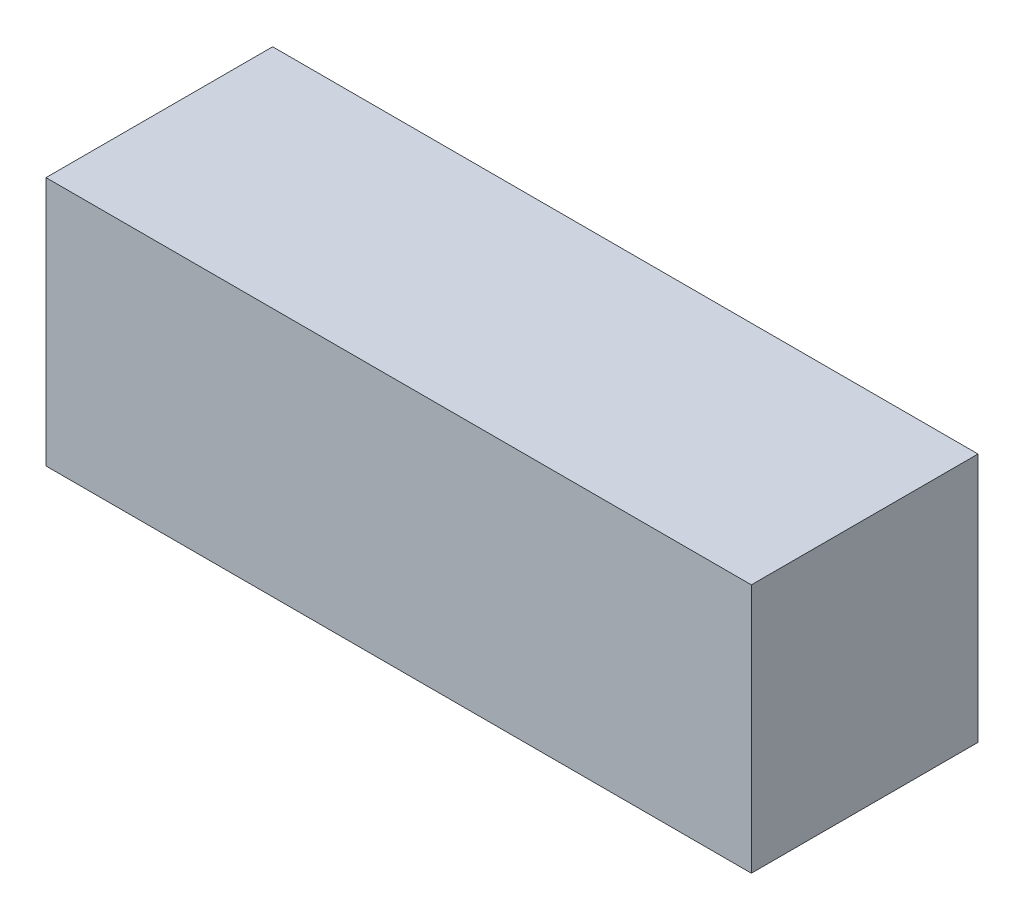
SolidWorks part; units mm, degrees
ref_plane "Front Plane" through (0, 0, 0) normal (0, 0, 1) x (1, 0, 0)
ref_plane "Top Plane" through (0, 0, 0) normal (0, 1, 0) x (1, 0, 0)
ref_plane "Right Plane" through (0, 0, 0) normal (1, 0, 0) x (0, 0, -1)
sketch "Sketch1" plane through (0, 0, 0) normal (0, 1, 0) x (1, 0, 0)
  line L1 (0, 0) -> (154.94, 0)
  line L2 (0, 0) -> (0, 49.784)
  line L3 (0, 49.784) -> (154.94, 49.784)
  line L4 (154.94, 0) -> (154.94, 49.784)
  dimension "D1" = 49.784
  dimension "D2" = 154.94
extrude "Boss-Extrude1" add sketch "Sketch1" along normal blind 54.864
